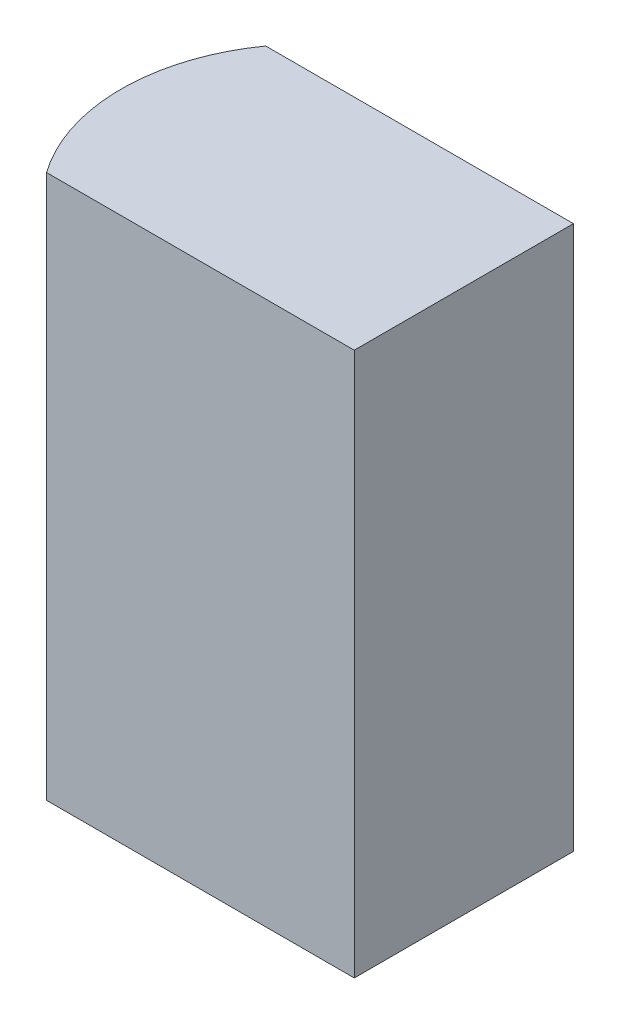
SolidWorks part; units mm, degrees
ref_plane "Front Plane" through (0, 0, 0) normal (0, 0, 1) x (1, 0, 0)
ref_plane "Top Plane" through (0, 0, 0) normal (0, 1, 0) x (1, 0, 0)
ref_plane "Right Plane" through (0, 0, 0) normal (1, 0, 0) x (0, 0, -1)
sketch "Sketch1" plane through (0, 0, 0) normal (0, 1, 0) x (1, 0, 0)
  line L1 (-182.5, -130) -> (182.5, -130)
  line L3 (-182.5, 130) -> (182.5, 130)
  line L4 (182.5, -130) -> (182.5, 130)
  line L5 (-182.5, -130) -> (182.5, 130) construction
  line L6 (-182.5, 130) -> (182.5, -130) construction
  arc A0 (-182.5, 130) -> (-182.5, -130) centre (0, 0) ccw
  point P0 (0, 0)
  point P7 (0, 0)
  point P8 (0, 0)
  dimension "D2" = 182.5
  dimension "D1" = 260
extrude "Boss-Extrude1" add sketch "Sketch1" along normal blind 645
